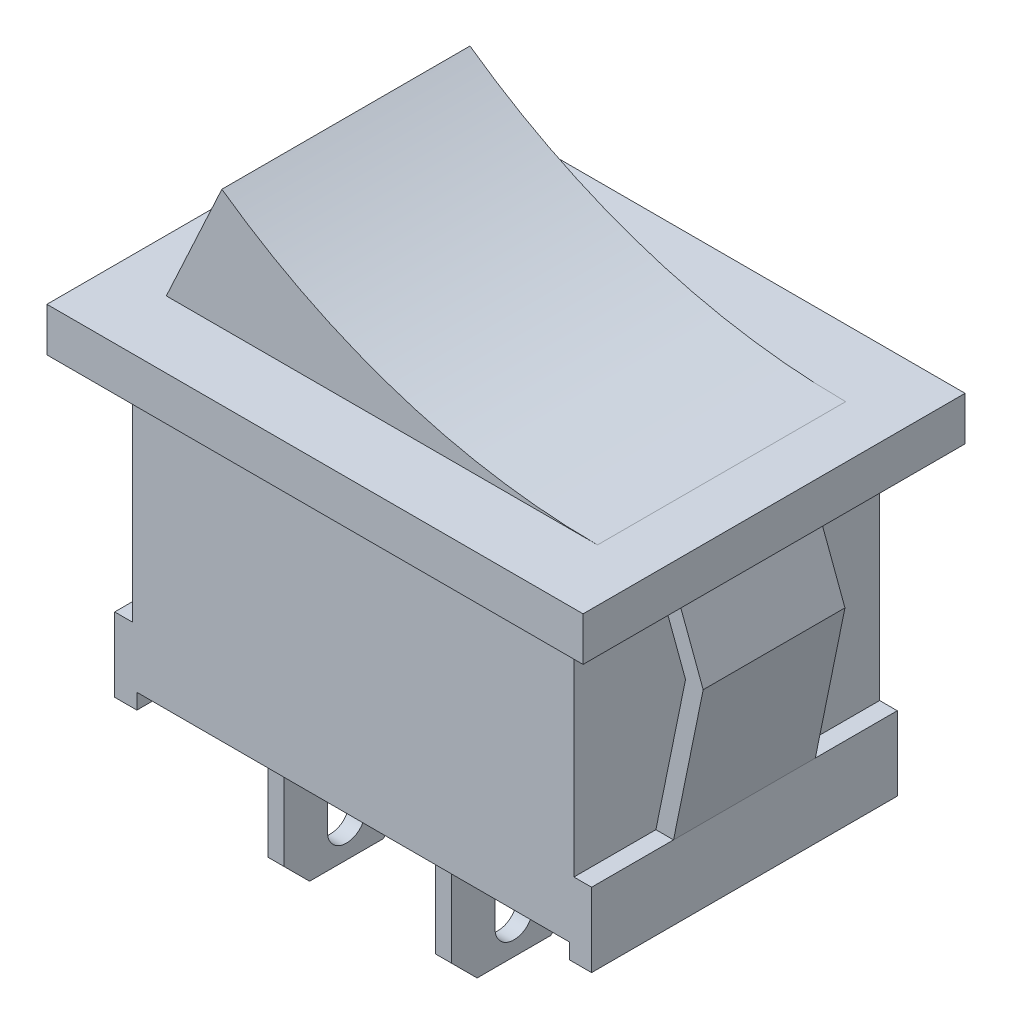
SolidWorks part; units mm, degrees
ref_plane "Front Plane" through (0, 0, 0) normal (0, 0, 1) x (1, 0, 0)
ref_plane "Top Plane" through (0, 0, 0) normal (0, 1, 0) x (1, 0, 0)
ref_plane "Right Plane" through (0, 0, 0) normal (1, 0, 0) x (0, 0, -1)
sketch "Sketch1" plane through (0, 0, 0) normal (0, 0, 1) x (1, 0, 0)
  line L0 (8.39, -6.985) -> (9.25, -6.985)
  line L5 (9.25, -6.985) -> (9.25, -4.115)
  line L6 (9.25, -4.115) -> (8.565, -4.115)
  line L7 (8.565, -4.115) -> (8.565, 4.685)
  line L8 (8.565, 4.685) -> (10.4, 4.685)
  line L9 (10.4, 4.685) -> (10.4, 6.385)
  line L10 (10.4, 6.385) -> (-10.4, 6.385)
  line L11 (0, 6.385) -> (0, -6.385) construction
  line L12 (8.39, -6.985) -> (8.39, -6.385)
  line L13 (8.39, -6.385) -> (-8.39, -6.385)
  line L14 (-8.39, -6.985) -> (-8.39, -6.385)
  line L15 (-10.4, 4.685) -> (-10.4, 6.385)
  line L16 (-8.565, 4.685) -> (-10.4, 4.685)
  line L17 (-8.565, -4.115) -> (-8.565, 4.685)
  line L18 (-9.25, -4.115) -> (-8.565, -4.115)
  line L19 (-9.25, -6.985) -> (-9.25, -4.115)
  line L20 (-8.39, -6.985) -> (-9.25, -6.985)
  point P0 (0, 0)
  dimension "D1" = 8.565
  dimension "D2" = 9.25
  dimension "D3" = 10.4
  dimension "D4" = 2.87
  dimension "D5" = 13.37
  dimension "D6" = 1.7
  dimension "D7" = 0.86
  dimension "D8" = 0.6
extrude "Boss-Extrude1" add sketch "Sketch1" along normal mid plane 14.82
sketch "Sketch2" plane through (0, 0, 0) normal (1, 0, 0) x (0, 0, -1)
  line L0 (-7.41, 4.685) -> (-5.93, 4.685)
  line L1 (-7.41, 4.685) -> (7.41, 4.685) construction
  line L2 (-5.93, 4.685) -> (-5.93, -6.985)
  line L3 (-7.41, -6.985) -> (7.41, -6.985) construction
  line L4 (-5.93, -6.985) -> (-7.41, -6.985)
  line L5 (-7.41, -6.985) -> (-7.41, 4.685)
  line L6 (7.41, 4.685) -> (5.93, 4.685)
  line L7 (5.93, 4.685) -> (5.93, -6.985)
  line L8 (5.93, -6.985) -> (7.41, -6.985)
  line L9 (7.41, -6.985) -> (7.41, 4.685)
  dimension "D1" = 11.86
extrude "Cut-Extrude1" cut sketch "Sketch2" against normal through all and the other way through all
sketch "Sketch3" plane through (0, 0, 0) normal (0, 0, 1) x (1, 0, 0)
  line L0 (9.25, -4.115) -> (10.4, 1.5057)
  line L1 (10.4, 1.5057) -> (9.2084, 4.685)
  line L2 (-10.4, 4.685) -> (10.4, 4.685) construction
  line L3 (9.2084, 4.685) -> (8.565, 4.685)
  line L4 (8.565, 4.685) -> (8.565, 4.5741)
  line L5 (8.565, 4.685) -> (8.565, -4.115) construction
  line L6 (8.565, 4.5741) -> (9.715, 1.5057)
  line L7 (9.715, 1.5057) -> (8.565, -4.115)
  line L8 (8.565, -4.115) -> (9.25, -4.115)
  line L9 (10.4, 4.685) -> (10.4, 6.385) construction
  line L10 (0, 0) -> (0, 6.385) construction
  line L11 (10.4, 6.385) -> (-10.4, 6.385) construction
  line L12 (-8.565, -4.115) -> (-9.25, -4.115)
  line L13 (-9.715, 1.5057) -> (-8.565, -4.115)
  line L14 (-8.565, 4.5741) -> (-9.715, 1.5057)
  line L15 (-8.565, 4.685) -> (-8.565, 4.5741)
  line L16 (-9.2084, 4.685) -> (-8.565, 4.685)
  line L17 (-10.4, 1.5057) -> (-9.2084, 4.685)
  line L18 (-9.25, -4.115) -> (-10.4, 1.5057)
extrude "Boss-Extrude2" add sketch "Sketch3" along normal mid plane 5.5
sketch "Sketch4" plane through (0, 0, 0) normal (0, 0, 1) x (1, 0, 0)
  line L0 (10.4, 6.385) -> (-10.4, 6.385) construction
  line L1 (-6.2102, 11.0465) -> (-8.365, 6.385)
  line L2 (-8.365, 6.385) -> (8.365, 6.385)
  line L3 (8.565, 4.685) -> (8.565, -4.115) construction
  line L4 (-8.565, -4.115) -> (-8.565, 4.685) construction
  arc A0 (8.365, 6.385) -> (-6.2102, 11.0465) centre (8.365, 31.502) cw
  point P10 (-7.3042, 12.2474)
  point P11 (-6.2102, 10.2145)
  point P14 (-6.2102, 11.0465)
  dimension "D1" = 0.2
  dimension "D2" = 0.2
extrude "Boss-Extrude3" add sketch "Sketch4" along normal mid plane 9.625
sketch "Sketch6" plane through (0, 0, 0) normal (1, 0, 0) x (0, 0, -1)
  line L0 (-2.43, -6.385) -> (-2.43, -12.885)
  line L1 (-5.93, -6.385) -> (5.93, -6.385) construction
  line L2 (-1.43, -13.885) -> (1.43, -13.885)
  line L3 (2.43, -12.885) -> (2.43, -6.385)
  line L4 (2.43, -6.385) -> (-2.43, -6.385)
  line L5 (0, -10.5836) -> (0, -12.5836) construction
  line L6 (0.7353, -10.5836) -> (0.7353, -12.5836)
  line L7 (-0.7353, -10.5836) -> (-0.7353, -12.5836)
  line L8 (1.43, -13.885) -> (2.43, -12.885)
  line L9 (-2.43, -12.885) -> (-1.43, -13.885)
  circle A0 centre (0, -8.6279) radius 0.8201
  arc A1 (0.7353, -10.5836) -> (-0.7353, -10.5836) centre (0, -10.5836) ccw
  arc A2 (-0.7353, -12.5836) -> (0.7353, -12.5836) centre (0, -12.5836) ccw
  point P1 (-2.43, -13.885)
  point P4 (0, -6.385)
  point P5 (2.43, -13.885)
  point P12 (0, -11.5836)
  point P17 (0, -11.9237)
  point P22 (0, 0)
  point P23 (0, -11.5836)
  dimension "D3" = 2
  dimension "D1" = 4.86
  dimension "D2" = 7.5
extrude "Boss-Extrude4" add sketch "Sketch6" along normal mid plane 0.62
pattern_linear "LPattern1" count 2 spacing 6.5 along (-1, 0, 0) of "Boss-Extrude4"
